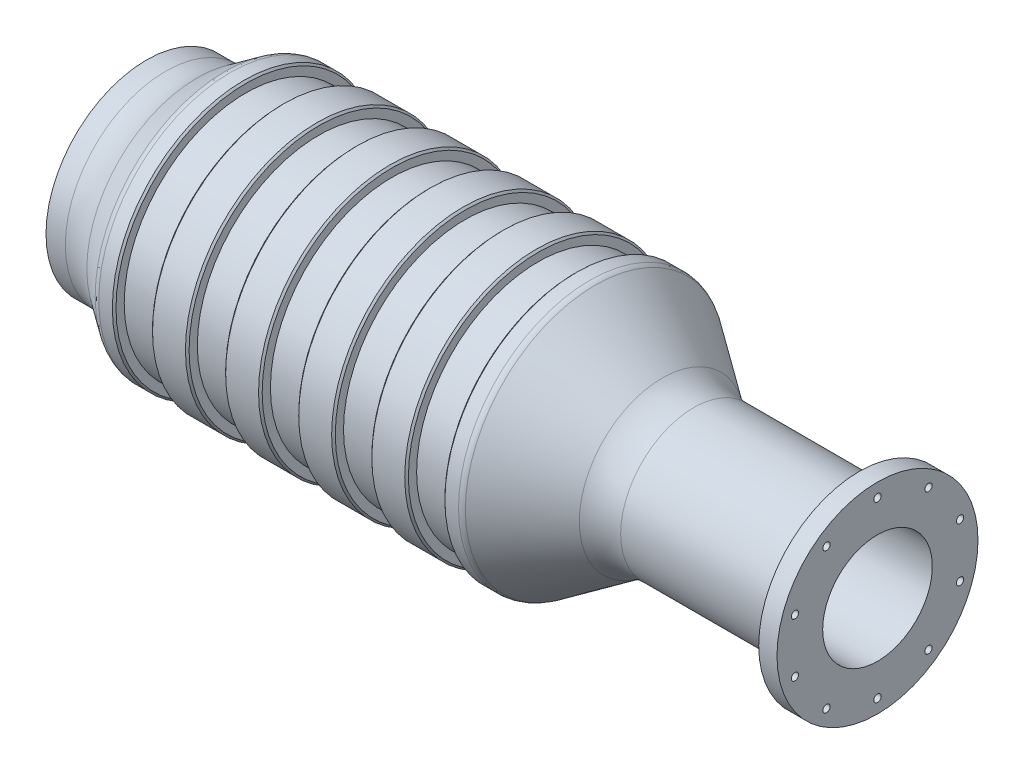
SolidWorks part; units mm, degrees
ref_plane "Front Plane" through (0, 0, 0) normal (0, 0, 1) x (1, 0, 0)
ref_plane "Top Plane" through (0, 0, 0) normal (0, 1, 0) x (1, 0, 0)
ref_plane "Right Plane" through (0, 0, 0) normal (1, 0, 0) x (0, 0, -1)
sketch "Sketch1" plane through (0, 0, 0) normal (0, 0, 1) x (1, 0, 0)
  line L0 (-41.9229, 0) -> (90.6931, 0) construction
  line L2 (200, 30) -> (93.153, 30)
  line L3 (81.6815, 33.617) -> (44.8837, 59.383)
  line L4 (33.4122, 63) -> (-144.8136, 63)
  line L5 (-156.2852, 59.383) -> (-171.6607, 48.617)
  line L6 (-183.1322, 45) -> (-185, 45)
  line L7 (-190, 40) -> (-190, 25)
  line L8 (-190, 25) -> (-200, 25)
  line L9 (-200, 25) -> (-200, 55)
  line L10 (-200, 55) -> (-179.9793, 55)
  line L11 (-179.9793, 55) -> (-155.7007, 72)
  line L12 (-155.7007, 72) -> (-145.7007, 72)
  line L13 (-145.7007, 72) -> (-145.7007, 66.5)
  line L14 (-145.7007, 66.5) -> (-125.7007, 66.5)
  line L15 (-125.7007, 66.5) -> (-125.7007, 72)
  line L16 (-125.7007, 72) -> (-105.7007, 72)
  line L17 (-105.7007, 72) -> (-105.7007, 66.5)
  line L18 (-105.7007, 66.5) -> (-85.7007, 66.5)
  line L19 (-85.7007, 66.5) -> (-85.7007, 72)
  line L20 (-85.7007, 72) -> (-65.7007, 72)
  line L21 (-65.7007, 72) -> (-65.7007, 66.5)
  line L22 (-65.7007, 66.5) -> (-45.7007, 66.5)
  line L23 (-45.7007, 66.5) -> (-45.7007, 72)
  line L24 (-45.7007, 72) -> (-25.7007, 72)
  line L25 (-25.7007, 72) -> (-25.7007, 66.5)
  line L26 (-25.7007, 66.5) -> (-5.7007, 66.5)
  line L27 (-5.7007, 66.5) -> (-5.7007, 72)
  line L28 (-5.7007, 72) -> (14.2993, 72)
  line L29 (14.2993, 72) -> (14.2993, 66.5)
  line L30 (14.2993, 66.5) -> (34.2993, 66.5)
  line L31 (34.2993, 66.5) -> (34.2993, 72)
  line L32 (34.2993, 72) -> (44.2993, 72)
  line L33 (44.2993, 72) -> (90, 40)
  line L34 (90, 40) -> (190, 40)
  line L35 (190, 40) -> (190, 55)
  line L36 (190, 55) -> (200, 55)
  line L37 (200, 55) -> (200, 30)
  arc A0 (93.153, 30) -> (81.6815, 33.617) centre (93.153, 50) cw
  arc A1 (44.8837, 59.383) -> (33.4122, 63) centre (33.4122, 43) ccw
  arc A2 (-144.8136, 63) -> (-156.2852, 59.383) centre (-144.8136, 43) ccw
  arc A3 (-171.6607, 48.617) -> (-183.1322, 45) centre (-183.1322, 65) cw
  arc A4 (-185, 45) -> (-190, 40) centre (-185, 40) ccw
  point P53 (-189.9896, 55)
  dimension "D23" = 20
  dimension "D24" = 5
  dimension "D1" = 10
  dimension "D2" = 10
  dimension "D3" = 10
  dimension "D4" = 100
  dimension "D5" = 20
  dimension "D6" = 20
  dimension "D7" = 5.5
  dimension "D8" = 3.5
  dimension "D9" = 10
  dimension "D10" = 10
  dimension "D11" = 10
  dimension "D12" = 145
  dimension "D13" = 30
  dimension "D14" = 55
  dimension "D15" = 200
  dimension "D16" = 55
  dimension "D17" = 25
  dimension "D18" = 145
  dimension "D19" = 72
  dimension "D20" = 10
  dimension "D21" = 400
  dimension "D22" = 200
revolve "Revolve1" add sketch "Sketch1" angle 360 about L0
fillet "Fillet1" radius 30 2 edges at (-179.9793, 0, 55) (90, 0, 40)
chamfer "Chamfer1" distance 1 angle 45 10 edges at (-125.7007, 0, 72) (-85.7007, 0, 72) (-45.7007, 0, 72) (-5.7007, 0, 72) (34.2993, 0, 72) (14.2993, 0, 72) (-25.7007, 0, 72) (-65.7007, 0, 72) (-105.7007, 0, 72) (-145.7007, 0, 72)
fillet "Fillet2" radius 5 3 edges at (190, 0, 40) (44.2993, 0, 72) (-155.7007, 0, 72)
sketch "Sketch2" plane through (-200, 0, 0) normal (-1, 0, 0) x (0, 0, 1)
  circle A0 centre (0, 45) radius 2
  dimension "D1" = 4
  dimension "D2" = 45
extrude "Cut-Extrude1" cut sketch "Sketch2" against normal blind 10
sketch "Sketch3" plane through (200, 0, 0) normal (1, 0, 0) x (0, 0, -1)
  circle A0 centre (0, 47.5) radius 2
  dimension "D1" = 4
  dimension "D2" = 47.5
extrude "Cut-Extrude2" cut sketch "Sketch3" against normal blind 10
pattern_circular "CirPattern1" count 10 over 360 about axis through (0, 0, 0) along (1, 0, 0) of "Cut-Extrude2", "Cut-Extrude1"
